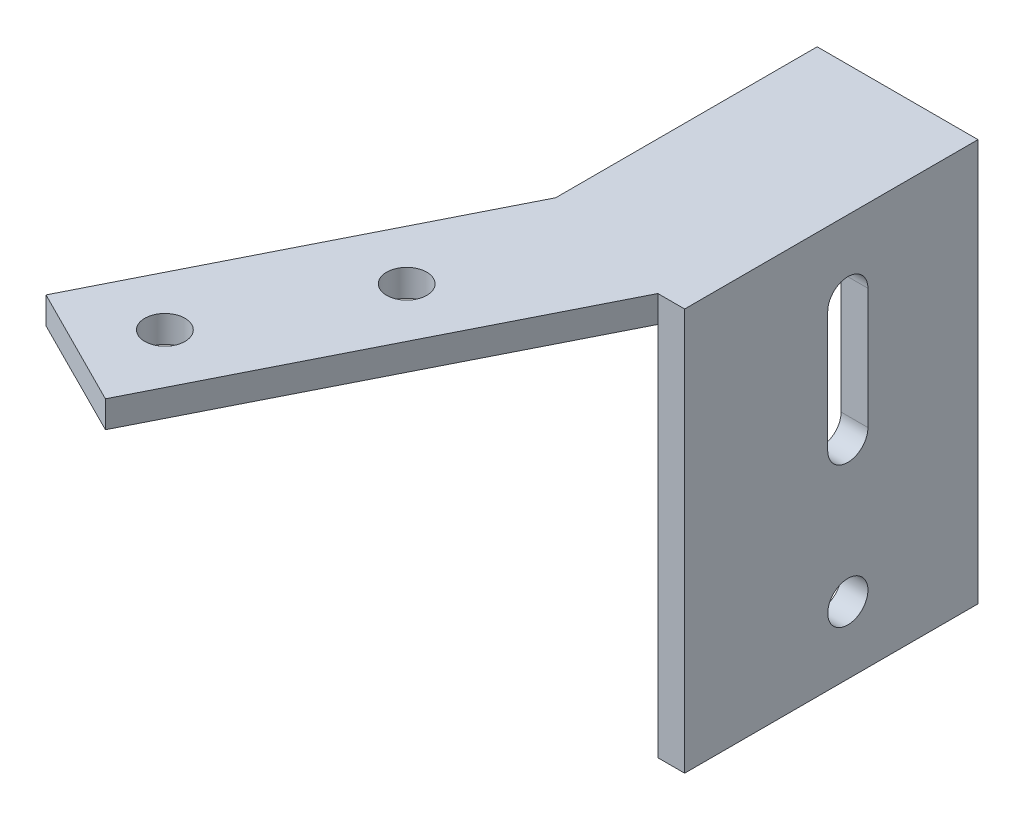
SolidWorks part; units mm, degrees
ref_plane "Front Plane" through (0, 0, 0) normal (0, 0, 1) x (1, 0, 0)
ref_plane "Top Plane" through (0, 0, 0) normal (0, 1, 0) x (1, 0, 0)
ref_plane "Right Plane" through (0, 0, 0) normal (1, 0, 0) x (0, 0, -1)
sketch "Sketch1" plane through (0, 0, 0) normal (0, 1, 0) x (1, 0, 0)
  line L5 (10.0186, 30.6) -> (10.0186, 8.7113)
  line L12 (0.0186, -0.0292) -> (0.0186, -16.455) construction
  line L18 (0.0186, 30.6) -> (10.0186, 30.6)
  line L20 (-8.2535, -16.455) -> (0.0186, -0.0292)
  line L21 (-3.7879, -18.7039) -> (10.0186, 8.7113)
  line L22 (-12.7192, -14.2061) -> (0.0186, 11.0872)
  line L23 (0.0186, -0.0292) -> (0.0186, -16.455) construction
  line L24 (-3.7879, -18.7039) -> (4.4842, -2.2781) construction
  line L25 (-12.7192, -14.2061) -> (-3.7879, -18.7039)
  line L27 (-12.7192, -14.2061) -> (-4.4471, 2.2197) construction
  line L28 (0.0186, 11.0872) -> (0.0186, 30.6)
  circle A0 centre (0.0186, -0.0292) radius 1.5
  circle A1 centre (-6.0247, -12.0292) radius 1.5
  point P0 (0, 0)
  point P10 (10.9989, 20.6)
  dimension "D1" = 3
  dimension "D9" = 3
  dimension "D10" = 12
  dimension "D3" = 26.73
  dimension "D5" = 20.6
  dimension "D7" = 5
  dimension "D8" = 5
extrude "Boss-Extrude1" add sketch "Sketch1" along normal blind 2
sketch "Sketch2" plane through (0, 2, 0) normal (0, 1, 0) x (1, 0, 0)
  line L0 (10.0186, 30.6) -> (12.0186, 30.6)
  line L1 (12.0186, 30.6) -> (12.0186, 8.7113)
  line L2 (12.0186, 8.7113) -> (10.0186, 8.7113)
  line L3 (10.0186, 30.6) -> (10.0186, 8.7113)
  dimension "D1" = 2
extrude "Boss-Extrude2" add sketch "Sketch2" against normal blind 30
sketch "Sketch3" plane through (0, 2, 0) normal (0, 1, 0) x (1, 0, 0)
  line L0 (0, 0) -> (12.0186, 0)
  line L1 (12.0186, 0) -> (12.0186, 20.6)
  line L2 (12.0186, 8.7113) -> (12.0186, 30.6) construction
  line L3 (12.0186, 20.6) -> (0, 0)
  dimension "D1" = 20.6
sketch "Sketch4" plane through (12.0186, 0, 0) normal (1, 0, 0) x (0, 0, -1)
  line L0 (20.8862, 2) -> (20.8862, -28) construction
  line L1 (20.6, 2) -> (0, 2) construction
  line L2 (8.7113, -28) -> (30.6, -28) construction
  line L3 (20.8862, -3.5) -> (20.8862, -12.5) construction
  line L4 (22.3862, -3.5) -> (22.3862, -12.5)
  line L5 (19.3862, -3.5) -> (19.3862, -12.5)
  line L6 (8.7113, 2) -> (30.6, 2) construction
  circle A0 centre (20.8862, -23) radius 1.5
  arc A1 (22.3862, -3.5) -> (19.3862, -3.5) centre (20.8862, -3.5) ccw
  arc A2 (19.3862, -12.5) -> (22.3862, -12.5) centre (20.8862, -12.5) ccw
  point P10 (20.8862, -8)
  dimension "D2" = 1.5
  dimension "D3" = 3
  dimension "D1" = 9
  dimension "D4" = 10
  dimension "D5" = 5
extrude "Cut-Extrude1" cut sketch "Sketch4" against normal blind 30
